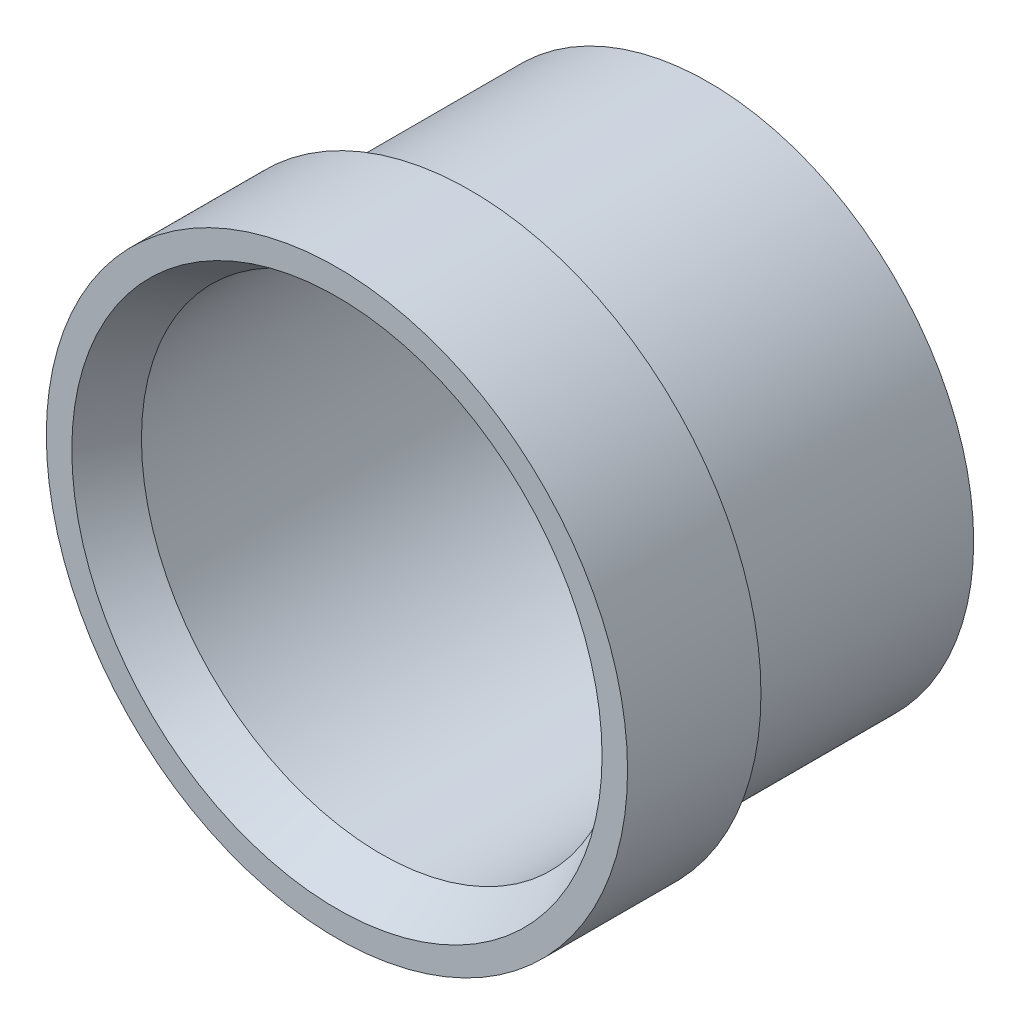
SolidWorks part; units mm, degrees
ref_plane "Front" through (0, 0, 0) normal (0, 0, 1) x (1, 0, 0)
ref_plane "Top" through (0, 0, 0) normal (0, 1, 0) x (1, 0, 0)
ref_plane "Right" through (0, 0, 0) normal (1, 0, 0) x (0, 0, -1)
sketch "Sketch1" plane through (0, 0, 0) normal (1, 0, 0) x (0, 0, -1)
  line L0 (-9.906, 14.1351) -> (-7.5523, 12.7762)
  line L1 (9.906, 12.7762) -> (9.906, 14.1351)
  line L2 (9.906, 14.1351) -> (-2.794, 14.1351)
  line L3 (-2.794, 14.1351) -> (-2.794, 15.494)
  line L4 (-2.794, 15.494) -> (-9.906, 15.494)
  line L5 (-9.906, 15.494) -> (-9.906, 14.1351)
  line L6 (-7.5523, 12.7762) -> (9.906, 12.7762)
  line L7 (9.906, 0) -> (-9.906, 0) construction
  dimension "D1" = 30
  dimension "Length" = 19.812
  dimension "Band" = 7.112
  dimension "Max OD" = 30.988
  dimension "ID" = 25.5524
revolve "Revolve1" add sketch "Sketch1" angle 360 about L7
